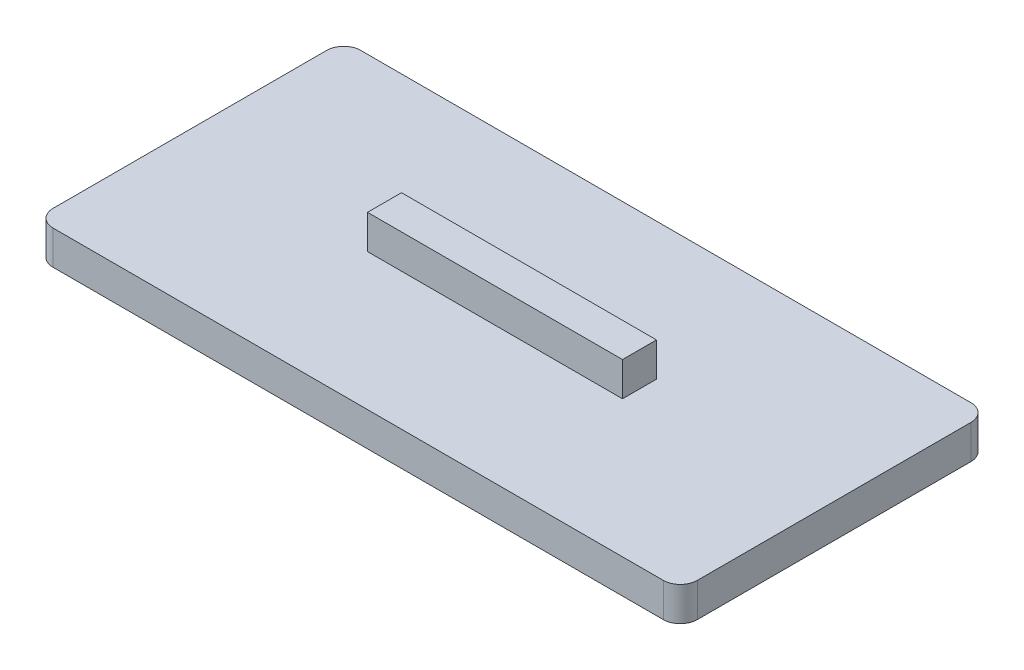
SolidWorks part; units mm, degrees
ref_plane "Front Plane" through (0, 0, 0) normal (0, 0, 1) x (1, 0, 0)
ref_plane "Top Plane" through (0, 0, 0) normal (0, 1, 0) x (1, 0, 0)
ref_plane "Right Plane" through (0, 0, 0) normal (1, 0, 0) x (0, 0, -1)
sketch "Sketch1" plane through (0, 0, 0) normal (0, 1, 0) x (1, 0, 0)
  line L1 (-22.7965, -11.4935) -> (22.7965, -11.4935)
  line L2 (-24.0665, -10.2235) -> (-24.0665, 10.2235)
  line L3 (-22.7965, 11.4935) -> (22.7965, 11.4935)
  line L4 (24.0665, -10.2235) -> (24.0665, 10.2235)
  line L5 (-24.0665, -11.4935) -> (24.0665, 11.4935) construction
  line L6 (-24.0665, 11.4935) -> (24.0665, -11.4935) construction
  arc A0 (-22.7965, -11.4935) -> (-24.0665, -10.2235) centre (-22.7965, -10.2235) cw
  arc A1 (22.7965, -11.4935) -> (24.0665, -10.2235) centre (22.7965, -10.2235) ccw
  arc A2 (22.7965, 11.4935) -> (24.0665, 10.2235) centre (22.7965, 10.2235) cw
  arc A3 (-24.0665, 10.2235) -> (-22.7965, 11.4935) centre (-22.7965, 10.2235) cw
  point P0 (0, 0)
  dimension "D3" = 1.27
  dimension "D1" = 22.987
  dimension "D2" = 48.133
extrude "Boss-Extrude1" add sketch "Sketch1" against normal blind 2.54
sketch "Sketch2" plane through (0, 0, 0) normal (0, 0, 1) x (1, 0, 0)
  line L0 (-9.525, 0) -> (-9.525, 2.54)
  line L1 (-22.7965, 0) -> (22.7965, 0) construction
  line L2 (9.525, 2.54) -> (9.525, 0)
  line L3 (9.525, 0) -> (-9.525, 0)
  line L4 (-9.525, 2.54) -> (9.525, 2.54)
  point P4 (0, 2.54)
  dimension "D1" = 2.54
  dimension "D2" = 19.05
extrude "Boss-Extrude2" add sketch "Sketch2" along normal mid plane 2.54
